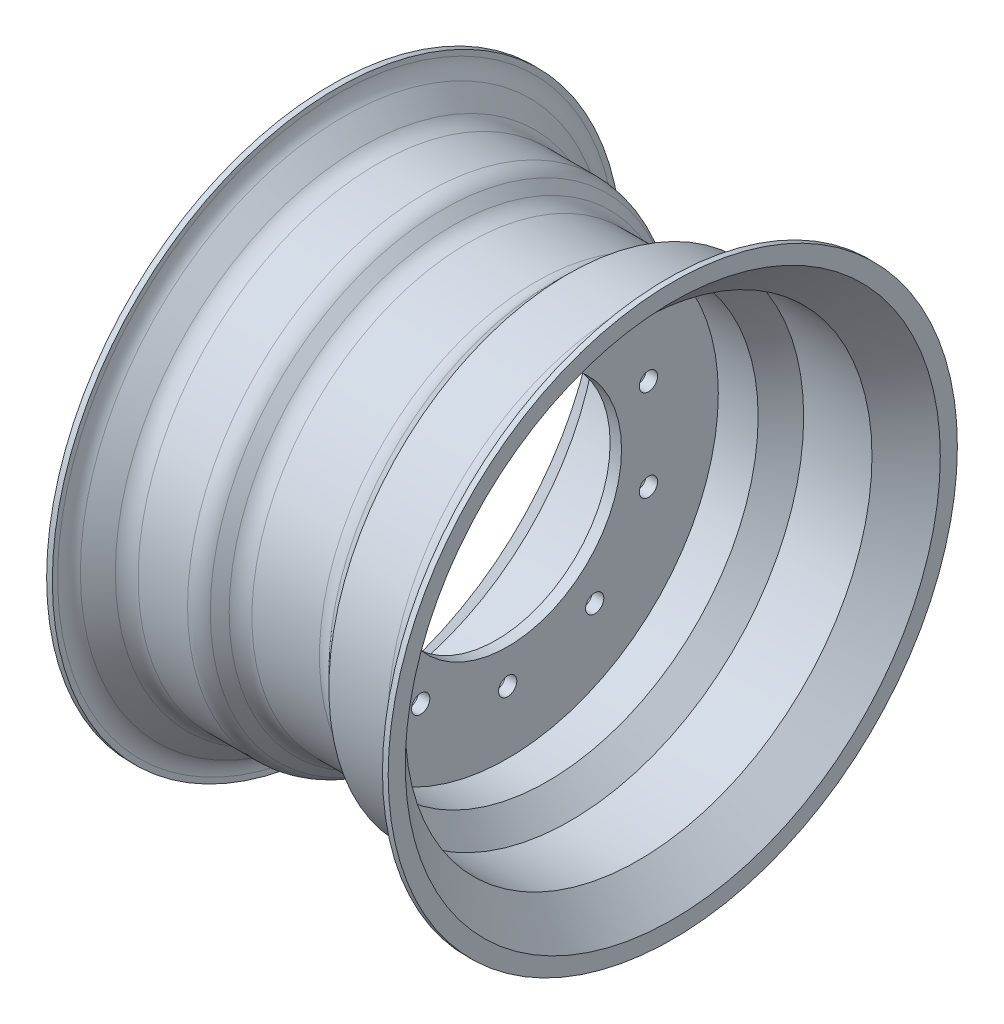
SolidWorks part; units mm, degrees
ref_plane "Front Plane" through (0, 0, 0) normal (0, 0, 1) x (1, 0, 0)
ref_plane "Top Plane" through (0, 0, 0) normal (0, 1, 0) x (1, 0, 0)
ref_plane "Right Plane" through (0, 0, 0) normal (1, 0, 0) x (0, 0, -1)
sketch "Sketch1" plane through (0, 0, 0) normal (0, 0, 1) x (1, 0, 0)
  line L0 (0, 0) -> (0, 195.5371) construction
  line L1 (0, 0) -> (-506.0514, 0) construction
  line L2 (-150, 250) -> (-150, 235)
  line L3 (-150, 235) -> (-120, 205)
  line L4 (-120, 205) -> (-60, 205)
  line L5 (-60, 205) -> (-40, 185)
  line L6 (-40, 185) -> (-5, 185)
  line L7 (60, 205) -> (40, 185)
  line L8 (120, 205) -> (60, 205)
  line L9 (150, 235) -> (120, 205)
  line L10 (150, 250) -> (150, 235)
  line L11 (-145, 250) -> (-145, 237.0711)
  line L12 (-145, 237.0711) -> (-117.9289, 210)
  line L13 (-117.9289, 210) -> (-57.9289, 210)
  line L14 (-57.9289, 210) -> (-37.9289, 190)
  line L15 (-37.9289, 190) -> (37.9289, 190)
  line L16 (57.9289, 210) -> (37.9289, 190)
  line L17 (117.9289, 210) -> (57.9289, 210)
  line L18 (145, 237.0711) -> (117.9289, 210)
  line L19 (145, 250) -> (145, 237.0711)
  line L20 (-150, 250) -> (-145, 250)
  line L21 (145, 250) -> (150, 250)
  line L22 (5, 185) -> (40, 185)
  line L23 (-5, 100) -> (5, 100)
  line L24 (-5, 100) -> (-5, 185)
  line L26 (5, 100) -> (5, 185)
  line L27 (-5, 100) -> (5, 185) construction
  line L28 (-5, 185) -> (5, 100) construction
  line L29 (-40, 185) -> (40, 185) construction
  point P11 (0, 185)
  point P25 (0, 142.5)
  dimension "D1" = 250
  dimension "D2" = 15
  dimension "D3" = 30
  dimension "D4" = 60
  dimension "D5" = 20
  dimension "D6" = 40
  dimension "D7" = 135
  dimension "D8" = 135
  dimension "D9" = 5
  dimension "D10" = 10
  dimension "D11" = 100
revolve "Revolve1" add sketch "Sketch1" angle 360 about L1
fillet "Fillet1" radius 20 7 edges at (37.9289, 0, -190) (145, 0, -237.0711) (117.9289, 0, -210) (-37.9289, 0, -190) (-57.9289, 0, -210) (-117.9289, 0, -210) (-145, 0, -237.0711)
sketch "Sketch2" plane through (5, 0, 0) normal (1, 0, 0) x (0, 0, -1)
  circle A0 centre (0, 130) radius 8
  dimension "D2" = 16
  dimension "D1" = 130
extrude "Cut-Extrude1" cut sketch "Sketch2" against normal blind 611
pattern_circular "CirPattern1" count 10 over 360 about axis through (0, 0, 0) along (1, 0, 0) of "Cut-Extrude1"
